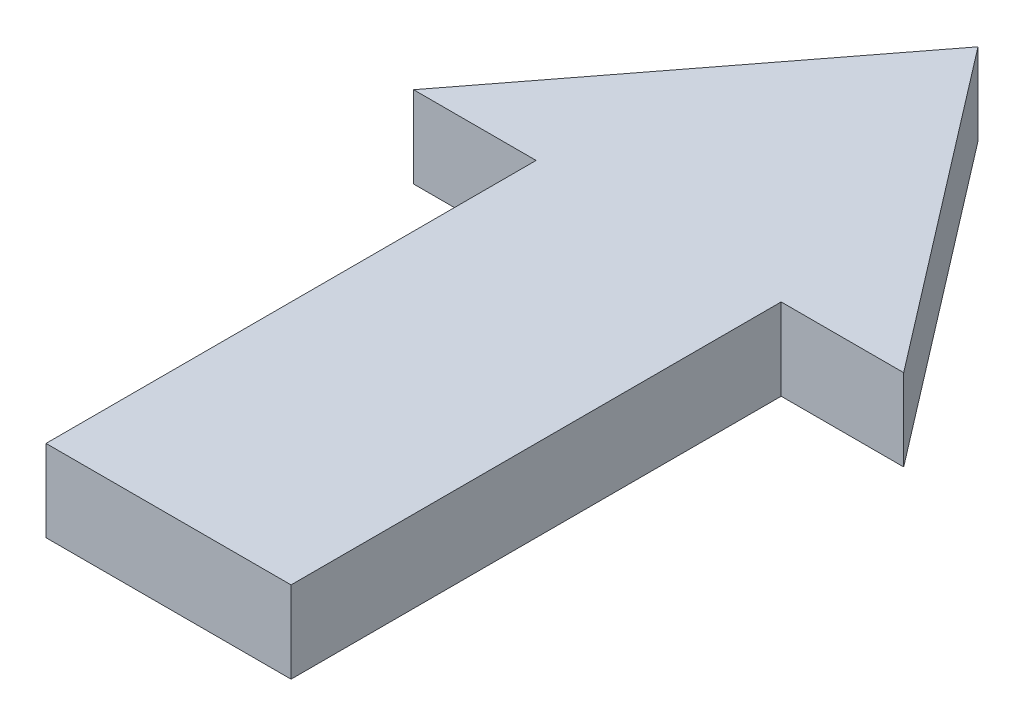
SolidWorks part; units mm, degrees
ref_plane "Front Plane" through (0, 0, 0) normal (0, 0, 1) x (1, 0, 0)
ref_plane "Top Plane" through (0, 0, 0) normal (0, 1, 0) x (1, 0, 0)
ref_plane "Right Plane" through (0, 0, 0) normal (1, 0, 0) x (0, 0, -1)
sketch "Sketch1" plane through (0, 0, 0) normal (0, 1, 0) x (1, 0, 0)
  line L0 (-76.2, 76.2) -> (76.2, 76.2)
  line L1 (-38.1, 76.2) -> (38.1, 76.2)
  line L2 (-38.1, 76.2) -> (-38.1, -76.2)
  line L3 (-38.1, -76.2) -> (38.1, -76.2)
  line L4 (38.1, 76.2) -> (38.1, -76.2)
  line L5 (-38.1, 76.2) -> (38.1, -76.2) construction
  line L6 (-38.1, -76.2) -> (38.1, 76.2) construction
  line L7 (0, 0) -> (0, 216.8912) construction
  line L8 (-76.2, 76.2) -> (0, 175.5058)
  line L9 (76.2, 76.2) -> (0, 175.5058)
  point P0 (0, 0)
  point P6 (0, 76.2)
  point P9 (0, 76.2)
  point P10 (0, 216.8912)
  dimension "D1" = 76.2
  dimension "D2" = 152.4
  dimension "D3" = 152.4
  dimension "D4" = 52.5
extrude "Boss-Extrude1" add sketch "Sketch1" along normal blind 25.4 contours L0 L9 L8 | L4 L0 L2 L3
